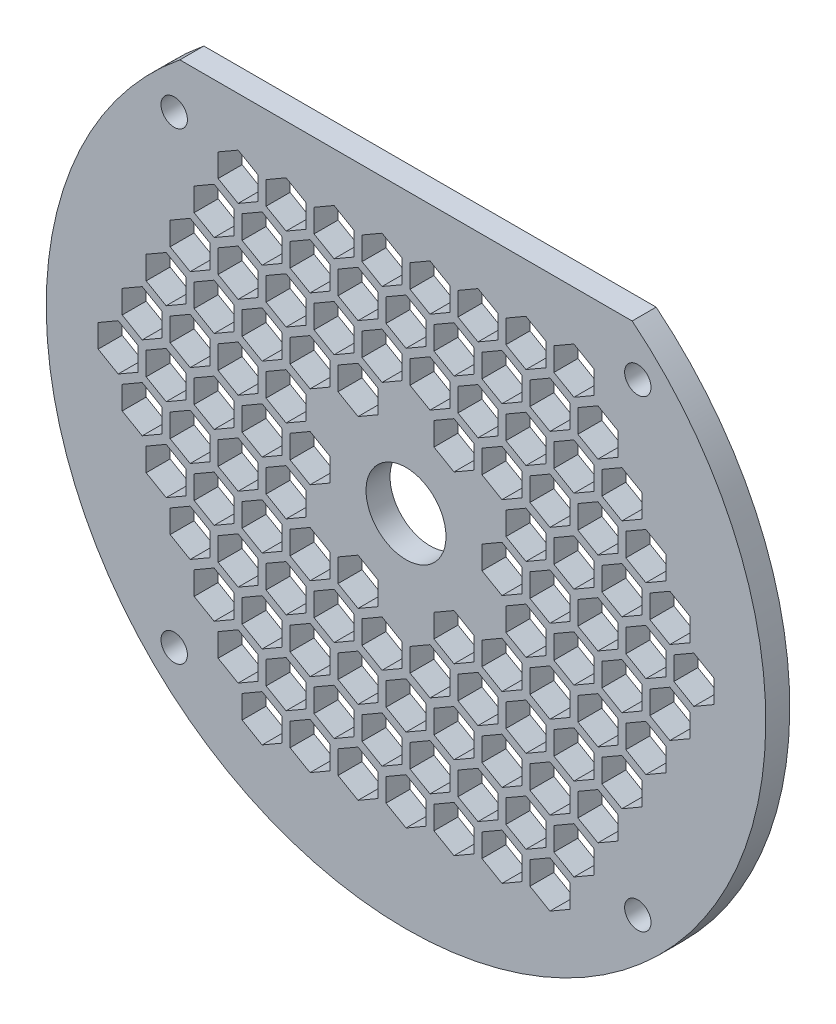
SolidWorks part; units mm, degrees
ref_plane "前视基准面" through (0, 0, 0) normal (0, 0, 1) x (1, 0, 0)
ref_plane "上视基准面" through (0, 0, 0) normal (0, 1, 0) x (1, 0, 0)
ref_plane "右视基准面" through (0, 0, 0) normal (1, 0, 0) x (0, 0, -1)
sketch "草图1" plane through (0, 0, 0) normal (0, 0, 1) x (1, 0, 0)
  circle A0 centre (0, 0) radius 90
extrude "凸台-拉伸1" add sketch "草图1" along normal blind 6
sketch "草图2" plane through (0, 0, 0) normal (0, 0, 1) x (1, 0, 0)
  line L0 (-200, 70) -> (200, 70)
  line L1 (200, 70) -> (200, 310)
  line L2 (200, 310) -> (-200, 310)
  line L3 (-200, 310) -> (-200, 70)
extrude "切除-拉伸1" cut sketch "草图2" along normal blind 6
sketch "草图3" plane through (0, 0, 0) normal (0, 0, 1) x (1, 0, 0)
  line L0 (24, 5.7735) -> (19, 2.8868)
  line L1 (19, 2.8868) -> (19, -2.8868)
  line L2 (19, -2.8868) -> (24, -5.7735)
  line L3 (24, -5.7735) -> (29, -2.8868)
  line L4 (29, -2.8868) -> (29, 2.8868)
  line L5 (29, 2.8868) -> (24, 5.7735)
  line L6 (-24, 5.7735) -> (-29, 2.8868)
  line L7 (-29, 2.8868) -> (-29, -2.8868)
  line L8 (-29, -2.8868) -> (-24, -5.7735)
  line L9 (-24, -5.7735) -> (-19, -2.8868)
  line L10 (-19, -2.8868) -> (-19, 2.8868)
  line L11 (-19, 2.8868) -> (-24, 5.7735)
  line L12 (36, 5.7735) -> (31, 2.8868)
  line L13 (31, 2.8868) -> (31, -2.8868)
  line L14 (31, -2.8868) -> (36, -5.7735)
  line L15 (36, -5.7735) -> (41, -2.8868)
  line L16 (41, -2.8868) -> (41, 2.8868)
  line L17 (41, 2.8868) -> (36, 5.7735)
  line L18 (-36, 5.7735) -> (-41, 2.8868)
  line L19 (-41, 2.8868) -> (-41, -2.8868)
  line L20 (-41, -2.8868) -> (-36, -5.7735)
  line L21 (-36, -5.7735) -> (-31, -2.8868)
  line L22 (-31, -2.8868) -> (-31, 2.8868)
  line L23 (-31, 2.8868) -> (-36, 5.7735)
  line L24 (48, 5.7735) -> (43, 2.8868)
  line L25 (43, 2.8868) -> (43, -2.8868)
  line L26 (43, -2.8868) -> (48, -5.7735)
  line L27 (48, -5.7735) -> (53, -2.8868)
  line L28 (53, -2.8868) -> (53, 2.8868)
  line L29 (53, 2.8868) -> (48, 5.7735)
  line L30 (-48, 5.7735) -> (-53, 2.8868)
  line L31 (-53, 2.8868) -> (-53, -2.8868)
  line L32 (-53, -2.8868) -> (-48, -5.7735)
  line L33 (-48, -5.7735) -> (-43, -2.8868)
  line L34 (-43, -2.8868) -> (-43, 2.8868)
  line L35 (-43, 2.8868) -> (-48, 5.7735)
  line L36 (60, 5.7735) -> (55, 2.8868)
  line L37 (55, 2.8868) -> (55, -2.8868)
  line L38 (55, -2.8868) -> (60, -5.7735)
  line L39 (60, -5.7735) -> (65, -2.8868)
  line L40 (65, -2.8868) -> (65, 2.8868)
  line L41 (65, 2.8868) -> (60, 5.7735)
  line L42 (-60, 5.7735) -> (-65, 2.8868)
  line L43 (-65, 2.8868) -> (-65, -2.8868)
  line L44 (-65, -2.8868) -> (-60, -5.7735)
  line L45 (-60, -5.7735) -> (-55, -2.8868)
  line L46 (-55, -2.8868) -> (-55, 2.8868)
  line L47 (-55, 2.8868) -> (-60, 5.7735)
  line L48 (72, 5.7735) -> (67, 2.8868)
  line L49 (67, 2.8868) -> (67, -2.8868)
  line L50 (67, -2.8868) -> (72, -5.7735)
  line L51 (72, -5.7735) -> (77, -2.8868)
  line L52 (77, -2.8868) -> (77, 2.8868)
  line L53 (77, 2.8868) -> (72, 5.7735)
  line L54 (-72, 5.7735) -> (-77, 2.8868)
  line L55 (-77, 2.8868) -> (-77, -2.8868)
  line L56 (-77, -2.8868) -> (-72, -5.7735)
  line L57 (-72, -5.7735) -> (-67, -2.8868)
  line L58 (-67, -2.8868) -> (-67, 2.8868)
  line L59 (-67, 2.8868) -> (-72, 5.7735)
  line L60 (30, 16.1655) -> (25, 13.2788)
  line L61 (25, 13.2788) -> (25, 7.5053)
  line L62 (25, 7.5053) -> (30, 4.6185)
  line L63 (30, 4.6185) -> (35, 7.5053)
  line L64 (35, 7.5053) -> (35, 13.2788)
  line L65 (35, 13.2788) -> (30, 16.1655)
  line L66 (-30, 16.1655) -> (-35, 13.2788)
  line L67 (-35, 13.2788) -> (-35, 7.5053)
  line L68 (-35, 7.5053) -> (-30, 4.6185)
  line L69 (-30, 4.6185) -> (-25, 7.5053)
  line L70 (-25, 7.5053) -> (-25, 13.2788)
  line L71 (-25, 13.2788) -> (-30, 16.1655)
  line L72 (42, 16.1655) -> (37, 13.2788)
  line L73 (37, 13.2788) -> (37, 7.5053)
  line L74 (37, 7.5053) -> (42, 4.6185)
  line L75 (42, 4.6185) -> (47, 7.5053)
  line L76 (47, 7.5053) -> (47, 13.2788)
  line L77 (47, 13.2788) -> (42, 16.1655)
  line L78 (-42, 16.1655) -> (-47, 13.2788)
  line L79 (-47, 13.2788) -> (-47, 7.5053)
  line L80 (-47, 7.5053) -> (-42, 4.6185)
  line L81 (-42, 4.6185) -> (-37, 7.5053)
  line L82 (-37, 7.5053) -> (-37, 13.2788)
  line L83 (-37, 13.2788) -> (-42, 16.1655)
  line L84 (54, 16.1655) -> (49, 13.2788)
  line L85 (49, 13.2788) -> (49, 7.5053)
  line L86 (49, 7.5053) -> (54, 4.6185)
  line L87 (54, 4.6185) -> (59, 7.5053)
  line L88 (59, 7.5053) -> (59, 13.2788)
  line L89 (59, 13.2788) -> (54, 16.1655)
  line L90 (-54, 16.1655) -> (-59, 13.2788)
  line L91 (-59, 13.2788) -> (-59, 7.5053)
  line L92 (-59, 7.5053) -> (-54, 4.6185)
  line L93 (-54, 4.6185) -> (-49, 7.5053)
  line L94 (-49, 7.5053) -> (-49, 13.2788)
  line L95 (-49, 13.2788) -> (-54, 16.1655)
  line L96 (66, 16.1655) -> (61, 13.2788)
  line L97 (61, 13.2788) -> (61, 7.5053)
  line L98 (61, 7.5053) -> (66, 4.6185)
  line L99 (66, 4.6185) -> (71, 7.5053)
  line L100 (71, 7.5053) -> (71, 13.2788)
  line L101 (71, 13.2788) -> (66, 16.1655)
  line L102 (-66, 16.1655) -> (-71, 13.2788)
  line L103 (-71, 13.2788) -> (-71, 7.5053)
  line L104 (-71, 7.5053) -> (-66, 4.6185)
  line L105 (-66, 4.6185) -> (-61, 7.5053)
  line L106 (-61, 7.5053) -> (-61, 13.2788)
  line L107 (-61, 13.2788) -> (-66, 16.1655)
  line L108 (30, -4.6185) -> (25, -7.5053)
  line L109 (25, -7.5053) -> (25, -13.2788)
  line L110 (25, -13.2788) -> (30, -16.1655)
  line L111 (30, -16.1655) -> (35, -13.2788)
  line L112 (35, -13.2788) -> (35, -7.5053)
  line L113 (35, -7.5053) -> (30, -4.6185)
  line L114 (-30, -4.6185) -> (-35, -7.5053)
  line L115 (-35, -7.5053) -> (-35, -13.2788)
  line L116 (-35, -13.2788) -> (-30, -16.1655)
  line L117 (-30, -16.1655) -> (-25, -13.2788)
  line L118 (-25, -13.2788) -> (-25, -7.5053)
  line L119 (-25, -7.5053) -> (-30, -4.6185)
  line L120 (42, -4.6185) -> (37, -7.5053)
  line L121 (37, -7.5053) -> (37, -13.2788)
  line L122 (37, -13.2788) -> (42, -16.1655)
  line L123 (42, -16.1655) -> (47, -13.2788)
  line L124 (47, -13.2788) -> (47, -7.5053)
  line L125 (47, -7.5053) -> (42, -4.6185)
  line L126 (-42, -4.6185) -> (-47, -7.5053)
  line L127 (-47, -7.5053) -> (-47, -13.2788)
  line L128 (-47, -13.2788) -> (-42, -16.1655)
  line L129 (-42, -16.1655) -> (-37, -13.2788)
  line L130 (-37, -13.2788) -> (-37, -7.5053)
  line L131 (-37, -7.5053) -> (-42, -4.6185)
  line L132 (54, -4.6185) -> (49, -7.5053)
  line L133 (49, -7.5053) -> (49, -13.2788)
  line L134 (49, -13.2788) -> (54, -16.1655)
  line L135 (54, -16.1655) -> (59, -13.2788)
  line L136 (59, -13.2788) -> (59, -7.5053)
  line L137 (59, -7.5053) -> (54, -4.6185)
  line L138 (-54, -4.6185) -> (-59, -7.5053)
  line L139 (-59, -7.5053) -> (-59, -13.2788)
  line L140 (-59, -13.2788) -> (-54, -16.1655)
  line L141 (-54, -16.1655) -> (-49, -13.2788)
  line L142 (-49, -13.2788) -> (-49, -7.5053)
  line L143 (-49, -7.5053) -> (-54, -4.6185)
  line L144 (66, -4.6185) -> (61, -7.5053)
  line L145 (61, -7.5053) -> (61, -13.2788)
  line L146 (61, -13.2788) -> (66, -16.1655)
  line L147 (66, -16.1655) -> (71, -13.2788)
  line L148 (71, -13.2788) -> (71, -7.5053)
  line L149 (71, -7.5053) -> (66, -4.6185)
  line L150 (-66, -4.6185) -> (-71, -7.5053)
  line L151 (-71, -7.5053) -> (-71, -13.2788)
  line L152 (-71, -13.2788) -> (-66, -16.1655)
  line L153 (-66, -16.1655) -> (-61, -13.2788)
  line L154 (-61, -13.2788) -> (-61, -7.5053)
  line L155 (-61, -7.5053) -> (-66, -4.6185)
extrude "切除-拉伸2" cut sketch "草图3" against normal mid plane 362
sketch "草图4" plane through (0, 0, 0) normal (0, 0, 1) x (1, 0, 0)
  line L0 (-60, 26.5575) -> (-65, 23.6708)
  line L1 (-65, 23.6708) -> (-65, 17.8972)
  line L2 (-65, 17.8972) -> (-60, 15.0105)
  line L3 (-60, 15.0105) -> (-55, 17.8972)
  line L4 (-55, 17.8972) -> (-55, 23.6708)
  line L5 (-55, 23.6708) -> (-60, 26.5575)
  line L6 (-48, 26.5575) -> (-53, 23.6708)
  line L7 (-53, 23.6708) -> (-53, 17.8972)
  line L8 (-53, 17.8972) -> (-48, 15.0105)
  line L9 (-48, 15.0105) -> (-43, 17.8972)
  line L10 (-43, 17.8972) -> (-43, 23.6708)
  line L11 (-43, 23.6708) -> (-48, 26.5575)
  line L12 (-36, 26.5575) -> (-41, 23.6708)
  line L13 (-41, 23.6708) -> (-41, 17.8972)
  line L14 (-41, 17.8972) -> (-36, 15.0105)
  line L15 (-36, 15.0105) -> (-31, 17.8972)
  line L16 (-31, 17.8972) -> (-31, 23.6708)
  line L17 (-31, 23.6708) -> (-36, 26.5575)
  line L18 (-24, 26.5575) -> (-29, 23.6708)
  line L19 (-29, 23.6708) -> (-29, 17.8972)
  line L20 (-29, 17.8972) -> (-24, 15.0105)
  line L21 (-24, 15.0105) -> (-19, 17.8972)
  line L22 (-19, 17.8972) -> (-19, 23.6708)
  line L23 (-19, 23.6708) -> (-24, 26.5575)
  line L24 (-12, 26.5575) -> (-17, 23.6708)
  line L25 (-17, 23.6708) -> (-17, 17.8972)
  line L26 (-17, 17.8972) -> (-12, 15.0105)
  line L27 (-12, 15.0105) -> (-7, 17.8972)
  line L28 (-7, 17.8972) -> (-7, 23.6708)
  line L29 (-7, 23.6708) -> (-12, 26.5575)
  line L30 (0, 26.5575) -> (-5, 23.6708)
  line L31 (-5, 23.6708) -> (-5, 17.8972)
  line L32 (-5, 17.8972) -> (0, 15.0105)
  line L33 (0, 15.0105) -> (5, 17.8972)
  line L34 (5, 17.8972) -> (5, 23.6708)
  line L35 (5, 23.6708) -> (0, 26.5575)
  line L36 (12, 26.5575) -> (7, 23.6708)
  line L37 (7, 23.6708) -> (7, 17.8972)
  line L38 (7, 17.8972) -> (12, 15.0105)
  line L39 (12, 15.0105) -> (17, 17.8972)
  line L40 (17, 17.8972) -> (17, 23.6708)
  line L41 (17, 23.6708) -> (12, 26.5575)
  line L42 (24, 26.5575) -> (19, 23.6708)
  line L43 (19, 23.6708) -> (19, 17.8972)
  line L44 (19, 17.8972) -> (24, 15.0105)
  line L45 (24, 15.0105) -> (29, 17.8972)
  line L46 (29, 17.8972) -> (29, 23.6708)
  line L47 (29, 23.6708) -> (24, 26.5575)
  line L48 (36, 26.5575) -> (31, 23.6708)
  line L49 (31, 23.6708) -> (31, 17.8972)
  line L50 (31, 17.8972) -> (36, 15.0105)
  line L51 (36, 15.0105) -> (41, 17.8972)
  line L52 (41, 17.8972) -> (41, 23.6708)
  line L53 (41, 23.6708) -> (36, 26.5575)
  line L54 (48, 26.5575) -> (43, 23.6708)
  line L55 (43, 23.6708) -> (43, 17.8972)
  line L56 (43, 17.8972) -> (48, 15.0105)
  line L57 (48, 15.0105) -> (53, 17.8972)
  line L58 (53, 17.8972) -> (53, 23.6708)
  line L59 (53, 23.6708) -> (48, 26.5575)
  line L60 (60, 26.5575) -> (55, 23.6708)
  line L61 (55, 23.6708) -> (55, 17.8972)
  line L62 (55, 17.8972) -> (60, 15.0105)
  line L63 (60, 15.0105) -> (65, 17.8972)
  line L64 (65, 17.8972) -> (65, 23.6708)
  line L65 (65, 23.6708) -> (60, 26.5575)
  line L66 (-60, -15.0105) -> (-65, -17.8972)
  line L67 (-65, -17.8972) -> (-65, -23.6708)
  line L68 (-65, -23.6708) -> (-60, -26.5575)
  line L69 (-60, -26.5575) -> (-55, -23.6708)
  line L70 (-55, -23.6708) -> (-55, -17.8972)
  line L71 (-55, -17.8972) -> (-60, -15.0105)
  line L72 (-48, -15.0105) -> (-53, -17.8972)
  line L73 (-53, -17.8972) -> (-53, -23.6708)
  line L74 (-53, -23.6708) -> (-48, -26.5575)
  line L75 (-48, -26.5575) -> (-43, -23.6708)
  line L76 (-43, -23.6708) -> (-43, -17.8972)
  line L77 (-43, -17.8972) -> (-48, -15.0105)
  line L78 (-36, -15.0105) -> (-41, -17.8972)
  line L79 (-41, -17.8972) -> (-41, -23.6708)
  line L80 (-41, -23.6708) -> (-36, -26.5575)
  line L81 (-36, -26.5575) -> (-31, -23.6708)
  line L82 (-31, -23.6708) -> (-31, -17.8972)
  line L83 (-31, -17.8972) -> (-36, -15.0105)
  line L84 (-24, -15.0105) -> (-29, -17.8972)
  line L85 (-29, -17.8972) -> (-29, -23.6708)
  line L86 (-29, -23.6708) -> (-24, -26.5575)
  line L87 (-24, -26.5575) -> (-19, -23.6708)
  line L88 (-19, -23.6708) -> (-19, -17.8972)
  line L89 (-19, -17.8972) -> (-24, -15.0105)
  line L90 (-12, -15.0105) -> (-17, -17.8972)
  line L91 (-17, -17.8972) -> (-17, -23.6708)
  line L92 (-17, -23.6708) -> (-12, -26.5575)
  line L93 (-12, -26.5575) -> (-7, -23.6708)
  line L94 (-7, -23.6708) -> (-7, -17.8972)
  line L95 (-7, -17.8972) -> (-12, -15.0105)
  line L96 (0, -15.0105) -> (-5, -17.8972)
  line L97 (-5, -17.8972) -> (-5, -23.6708)
  line L98 (-5, -23.6708) -> (0, -26.5575)
  line L99 (0, -26.5575) -> (5, -23.6708)
  line L100 (5, -23.6708) -> (5, -17.8972)
  line L101 (5, -17.8972) -> (0, -15.0105)
  line L102 (12, -15.0105) -> (7, -17.8972)
  line L103 (7, -17.8972) -> (7, -23.6708)
  line L104 (7, -23.6708) -> (12, -26.5575)
  line L105 (12, -26.5575) -> (17, -23.6708)
  line L106 (17, -23.6708) -> (17, -17.8972)
  line L107 (17, -17.8972) -> (12, -15.0105)
  line L108 (24, -15.0105) -> (19, -17.8972)
  line L109 (19, -17.8972) -> (19, -23.6708)
  line L110 (19, -23.6708) -> (24, -26.5575)
  line L111 (24, -26.5575) -> (29, -23.6708)
  line L112 (29, -23.6708) -> (29, -17.8972)
  line L113 (29, -17.8972) -> (24, -15.0105)
  line L114 (36, -15.0105) -> (31, -17.8972)
  line L115 (31, -17.8972) -> (31, -23.6708)
  line L116 (31, -23.6708) -> (36, -26.5575)
  line L117 (36, -26.5575) -> (41, -23.6708)
  line L118 (41, -23.6708) -> (41, -17.8972)
  line L119 (41, -17.8972) -> (36, -15.0105)
  line L120 (48, -15.0105) -> (43, -17.8972)
  line L121 (43, -17.8972) -> (43, -23.6708)
  line L122 (43, -23.6708) -> (48, -26.5575)
  line L123 (48, -26.5575) -> (53, -23.6708)
  line L124 (53, -23.6708) -> (53, -17.8972)
  line L125 (53, -17.8972) -> (48, -15.0105)
  line L126 (60, -15.0105) -> (55, -17.8972)
  line L127 (55, -17.8972) -> (55, -23.6708)
  line L128 (55, -23.6708) -> (60, -26.5575)
  line L129 (60, -26.5575) -> (65, -23.6708)
  line L130 (65, -23.6708) -> (65, -17.8972)
  line L131 (65, -17.8972) -> (60, -15.0105)
extrude "切除-拉伸3" cut sketch "草图4" against normal mid plane 362
sketch "草图5" plane through (0, 0, 0) normal (0, 0, 1) x (1, 0, 0)
  line L0 (0, 26.5575) -> (-5, 23.6708)
  line L1 (-5, 23.6708) -> (-5, 17.8972)
  line L2 (-5, 17.8972) -> (0, 15.0105)
  line L3 (0, 15.0105) -> (5, 17.8972)
  line L4 (5, 17.8972) -> (5, 23.6708)
  line L5 (5, 23.6708) -> (0, 26.5575)
  line L6 (0, -15.0105) -> (-5, -17.8972)
  line L7 (-5, -17.8972) -> (-5, -23.6708)
  line L8 (-5, -23.6708) -> (0, -26.5575)
  line L9 (0, -26.5575) -> (5, -23.6708)
  line L10 (5, -23.6708) -> (5, -17.8972)
  line L11 (5, -17.8972) -> (0, -15.0105)
extrude "凸台-拉伸2" add sketch "草图5" along normal blind 6
sketch "草图7" plane through (0, 0, 0) normal (0, 0, 1) x (1, 0, 0)
  line L0 (6, 36.9495) -> (1, 34.0628)
  line L1 (1, 34.0628) -> (1, 28.2892)
  line L2 (1, 28.2892) -> (6, 25.4025)
  line L3 (6, 25.4025) -> (11, 28.2892)
  line L4 (11, 28.2892) -> (11, 34.0628)
  line L5 (11, 34.0628) -> (6, 36.9495)
  line L6 (-6, 36.9495) -> (-11, 34.0628)
  line L7 (-11, 34.0628) -> (-11, 28.2892)
  line L8 (-11, 28.2892) -> (-6, 25.4025)
  line L9 (-6, 25.4025) -> (-1, 28.2892)
  line L10 (-1, 28.2892) -> (-1, 34.0628)
  line L11 (-1, 34.0628) -> (-6, 36.9495)
  line L12 (18, 36.9495) -> (13, 34.0628)
  line L13 (13, 34.0628) -> (13, 28.2892)
  line L14 (13, 28.2892) -> (18, 25.4025)
  line L15 (18, 25.4025) -> (23, 28.2892)
  line L16 (23, 28.2892) -> (23, 34.0628)
  line L17 (23, 34.0628) -> (18, 36.9495)
  line L18 (-18, 36.9495) -> (-23, 34.0628)
  line L19 (-23, 34.0628) -> (-23, 28.2892)
  line L20 (-23, 28.2892) -> (-18, 25.4025)
  line L21 (-18, 25.4025) -> (-13, 28.2892)
  line L22 (-13, 28.2892) -> (-13, 34.0628)
  line L23 (-13, 34.0628) -> (-18, 36.9495)
  line L24 (30, 36.9495) -> (25, 34.0628)
  line L25 (25, 34.0628) -> (25, 28.2892)
  line L26 (25, 28.2892) -> (30, 25.4025)
  line L27 (30, 25.4025) -> (35, 28.2892)
  line L28 (35, 28.2892) -> (35, 34.0628)
  line L29 (35, 34.0628) -> (30, 36.9495)
  line L30 (-30, 36.9495) -> (-35, 34.0628)
  line L31 (-35, 34.0628) -> (-35, 28.2892)
  line L32 (-35, 28.2892) -> (-30, 25.4025)
  line L33 (-30, 25.4025) -> (-25, 28.2892)
  line L34 (-25, 28.2892) -> (-25, 34.0628)
  line L35 (-25, 34.0628) -> (-30, 36.9495)
  line L36 (42, 36.9495) -> (37, 34.0628)
  line L37 (37, 34.0628) -> (37, 28.2892)
  line L38 (37, 28.2892) -> (42, 25.4025)
  line L39 (42, 25.4025) -> (47, 28.2892)
  line L40 (47, 28.2892) -> (47, 34.0628)
  line L41 (47, 34.0628) -> (42, 36.9495)
  line L42 (-42, 36.9495) -> (-47, 34.0628)
  line L43 (-47, 34.0628) -> (-47, 28.2892)
  line L44 (-47, 28.2892) -> (-42, 25.4025)
  line L45 (-42, 25.4025) -> (-37, 28.2892)
  line L46 (-37, 28.2892) -> (-37, 34.0628)
  line L47 (-37, 34.0628) -> (-42, 36.9495)
  line L48 (54, 36.9495) -> (49, 34.0628)
  line L49 (49, 34.0628) -> (49, 28.2892)
  line L50 (49, 28.2892) -> (54, 25.4025)
  line L51 (54, 25.4025) -> (59, 28.2892)
  line L52 (59, 28.2892) -> (59, 34.0628)
  line L53 (59, 34.0628) -> (54, 36.9495)
  line L54 (-54, 36.9495) -> (-59, 34.0628)
  line L55 (-59, 34.0628) -> (-59, 28.2892)
  line L56 (-59, 28.2892) -> (-54, 25.4025)
  line L57 (-54, 25.4025) -> (-49, 28.2892)
  line L58 (-49, 28.2892) -> (-49, 34.0628)
  line L59 (-49, 34.0628) -> (-54, 36.9495)
  line L60 (6, -25.4025) -> (1, -28.2892)
  line L61 (1, -28.2892) -> (1, -34.0628)
  line L62 (1, -34.0628) -> (6, -36.9495)
  line L63 (6, -36.9495) -> (11, -34.0628)
  line L64 (11, -34.0628) -> (11, -28.2892)
  line L65 (11, -28.2892) -> (6, -25.4025)
  line L66 (-6, -25.4025) -> (-11, -28.2892)
  line L67 (-11, -28.2892) -> (-11, -34.0628)
  line L68 (-11, -34.0628) -> (-6, -36.9495)
  line L69 (-6, -36.9495) -> (-1, -34.0628)
  line L70 (-1, -34.0628) -> (-1, -28.2892)
  line L71 (-1, -28.2892) -> (-6, -25.4025)
  line L72 (18, -25.4025) -> (13, -28.2892)
  line L73 (13, -28.2892) -> (13, -34.0628)
  line L74 (13, -34.0628) -> (18, -36.9495)
  line L75 (18, -36.9495) -> (23, -34.0628)
  line L76 (23, -34.0628) -> (23, -28.2892)
  line L77 (23, -28.2892) -> (18, -25.4025)
  line L78 (-18, -25.4025) -> (-23, -28.2892)
  line L79 (-23, -28.2892) -> (-23, -34.0628)
  line L80 (-23, -34.0628) -> (-18, -36.9495)
  line L81 (-18, -36.9495) -> (-13, -34.0628)
  line L82 (-13, -34.0628) -> (-13, -28.2892)
  line L83 (-13, -28.2892) -> (-18, -25.4025)
  line L84 (30, -25.4025) -> (25, -28.2892)
  line L85 (25, -28.2892) -> (25, -34.0628)
  line L86 (25, -34.0628) -> (30, -36.9495)
  line L87 (30, -36.9495) -> (35, -34.0628)
  line L88 (35, -34.0628) -> (35, -28.2892)
  line L89 (35, -28.2892) -> (30, -25.4025)
  line L90 (-30, -25.4025) -> (-35, -28.2892)
  line L91 (-35, -28.2892) -> (-35, -34.0628)
  line L92 (-35, -34.0628) -> (-30, -36.9495)
  line L93 (-30, -36.9495) -> (-25, -34.0628)
  line L94 (-25, -34.0628) -> (-25, -28.2892)
  line L95 (-25, -28.2892) -> (-30, -25.4025)
  line L96 (42, -25.4025) -> (37, -28.2892)
  line L97 (37, -28.2892) -> (37, -34.0628)
  line L98 (37, -34.0628) -> (42, -36.9495)
  line L99 (42, -36.9495) -> (47, -34.0628)
  line L100 (47, -34.0628) -> (47, -28.2892)
  line L101 (47, -28.2892) -> (42, -25.4025)
  line L102 (-42, -25.4025) -> (-47, -28.2892)
  line L103 (-47, -28.2892) -> (-47, -34.0628)
  line L104 (-47, -34.0628) -> (-42, -36.9495)
  line L105 (-42, -36.9495) -> (-37, -34.0628)
  line L106 (-37, -34.0628) -> (-37, -28.2892)
  line L107 (-37, -28.2892) -> (-42, -25.4025)
  line L108 (54, -25.4025) -> (49, -28.2892)
  line L109 (49, -28.2892) -> (49, -34.0628)
  line L110 (49, -34.0628) -> (54, -36.9495)
  line L111 (54, -36.9495) -> (59, -34.0628)
  line L112 (59, -34.0628) -> (59, -28.2892)
  line L113 (59, -28.2892) -> (54, -25.4025)
  line L114 (-54, -25.4025) -> (-59, -28.2892)
  line L115 (-59, -28.2892) -> (-59, -34.0628)
  line L116 (-59, -34.0628) -> (-54, -36.9495)
  line L117 (-54, -36.9495) -> (-49, -34.0628)
  line L118 (-49, -34.0628) -> (-49, -28.2892)
  line L119 (-49, -28.2892) -> (-54, -25.4025)
extrude "切除-拉伸6" cut sketch "草图7" against normal mid plane 362
sketch "草图8" plane through (0, 0, 0) normal (0, 0, 1) x (1, 0, 0)
  line L0 (0, 47.3415) -> (-5, 44.4547)
  line L1 (-5, 44.4547) -> (-5, 38.6812)
  line L2 (-5, 38.6812) -> (0, 35.7945)
  line L3 (0, 35.7945) -> (5, 38.6812)
  line L4 (5, 38.6812) -> (5, 44.4547)
  line L5 (5, 44.4547) -> (0, 47.3415)
  line L6 (12, 47.3415) -> (7, 44.4547)
  line L7 (7, 44.4547) -> (7, 38.6812)
  line L8 (7, 38.6812) -> (12, 35.7945)
  line L9 (12, 35.7945) -> (17, 38.6812)
  line L10 (17, 38.6812) -> (17, 44.4547)
  line L11 (17, 44.4547) -> (12, 47.3415)
  line L12 (-12, 47.3415) -> (-17, 44.4547)
  line L13 (-17, 44.4547) -> (-17, 38.6812)
  line L14 (-17, 38.6812) -> (-12, 35.7945)
  line L15 (-12, 35.7945) -> (-7, 38.6812)
  line L16 (-7, 38.6812) -> (-7, 44.4547)
  line L17 (-7, 44.4547) -> (-12, 47.3415)
  line L18 (24, 47.3415) -> (19, 44.4547)
  line L19 (19, 44.4547) -> (19, 38.6812)
  line L20 (19, 38.6812) -> (24, 35.7945)
  line L21 (24, 35.7945) -> (29, 38.6812)
  line L22 (29, 38.6812) -> (29, 44.4547)
  line L23 (29, 44.4547) -> (24, 47.3415)
  line L24 (-24, 47.3415) -> (-29, 44.4547)
  line L25 (-29, 44.4547) -> (-29, 38.6812)
  line L26 (-29, 38.6812) -> (-24, 35.7945)
  line L27 (-24, 35.7945) -> (-19, 38.6812)
  line L28 (-19, 38.6812) -> (-19, 44.4547)
  line L29 (-19, 44.4547) -> (-24, 47.3415)
  line L30 (36, 47.3415) -> (31, 44.4547)
  line L31 (31, 44.4547) -> (31, 38.6812)
  line L32 (31, 38.6812) -> (36, 35.7945)
  line L33 (36, 35.7945) -> (41, 38.6812)
  line L34 (41, 38.6812) -> (41, 44.4547)
  line L35 (41, 44.4547) -> (36, 47.3415)
  line L36 (-36, 47.3415) -> (-41, 44.4547)
  line L37 (-41, 44.4547) -> (-41, 38.6812)
  line L38 (-41, 38.6812) -> (-36, 35.7945)
  line L39 (-36, 35.7945) -> (-31, 38.6812)
  line L40 (-31, 38.6812) -> (-31, 44.4547)
  line L41 (-31, 44.4547) -> (-36, 47.3415)
  line L42 (48, 47.3415) -> (43, 44.4547)
  line L43 (43, 44.4547) -> (43, 38.6812)
  line L44 (43, 38.6812) -> (48, 35.7945)
  line L45 (48, 35.7945) -> (53, 38.6812)
  line L46 (53, 38.6812) -> (53, 44.4547)
  line L47 (53, 44.4547) -> (48, 47.3415)
  line L48 (-48, 47.3415) -> (-53, 44.4547)
  line L49 (-53, 44.4547) -> (-53, 38.6812)
  line L50 (-53, 38.6812) -> (-48, 35.7945)
  line L51 (-48, 35.7945) -> (-43, 38.6812)
  line L52 (-43, 38.6812) -> (-43, 44.4547)
  line L53 (-43, 44.4547) -> (-48, 47.3415)
  line L54 (0, -35.7945) -> (-5, -38.6812)
  line L55 (-5, -38.6812) -> (-5, -44.4547)
  line L56 (-5, -44.4547) -> (0, -47.3415)
  line L57 (0, -47.3415) -> (5, -44.4547)
  line L58 (5, -44.4547) -> (5, -38.6812)
  line L59 (5, -38.6812) -> (0, -35.7945)
  line L60 (12, -35.7945) -> (7, -38.6812)
  line L61 (7, -38.6812) -> (7, -44.4547)
  line L62 (7, -44.4547) -> (12, -47.3415)
  line L63 (12, -47.3415) -> (17, -44.4547)
  line L64 (17, -44.4547) -> (17, -38.6812)
  line L65 (17, -38.6812) -> (12, -35.7945)
  line L66 (-12, -35.7945) -> (-17, -38.6812)
  line L67 (-17, -38.6812) -> (-17, -44.4547)
  line L68 (-17, -44.4547) -> (-12, -47.3415)
  line L69 (-12, -47.3415) -> (-7, -44.4547)
  line L70 (-7, -44.4547) -> (-7, -38.6812)
  line L71 (-7, -38.6812) -> (-12, -35.7945)
  line L72 (24, -35.7945) -> (19, -38.6812)
  line L73 (19, -38.6812) -> (19, -44.4547)
  line L74 (19, -44.4547) -> (24, -47.3415)
  line L75 (24, -47.3415) -> (29, -44.4547)
  line L76 (29, -44.4547) -> (29, -38.6812)
  line L77 (29, -38.6812) -> (24, -35.7945)
  line L78 (-24, -35.7945) -> (-29, -38.6812)
  line L79 (-29, -38.6812) -> (-29, -44.4547)
  line L80 (-29, -44.4547) -> (-24, -47.3415)
  line L81 (-24, -47.3415) -> (-19, -44.4547)
  line L82 (-19, -44.4547) -> (-19, -38.6812)
  line L83 (-19, -38.6812) -> (-24, -35.7945)
  line L84 (36, -35.7945) -> (31, -38.6812)
  line L85 (31, -38.6812) -> (31, -44.4547)
  line L86 (31, -44.4547) -> (36, -47.3415)
  line L87 (36, -47.3415) -> (41, -44.4547)
  line L88 (41, -44.4547) -> (41, -38.6812)
  line L89 (41, -38.6812) -> (36, -35.7945)
  line L90 (-36, -35.7945) -> (-41, -38.6812)
  line L91 (-41, -38.6812) -> (-41, -44.4547)
  line L92 (-41, -44.4547) -> (-36, -47.3415)
  line L93 (-36, -47.3415) -> (-31, -44.4547)
  line L94 (-31, -44.4547) -> (-31, -38.6812)
  line L95 (-31, -38.6812) -> (-36, -35.7945)
  line L96 (48, -35.7945) -> (43, -38.6812)
  line L97 (43, -38.6812) -> (43, -44.4547)
  line L98 (43, -44.4547) -> (48, -47.3415)
  line L99 (48, -47.3415) -> (53, -44.4547)
  line L100 (53, -44.4547) -> (53, -38.6812)
  line L101 (53, -38.6812) -> (48, -35.7945)
  line L102 (-48, -35.7945) -> (-53, -38.6812)
  line L103 (-53, -38.6812) -> (-53, -44.4547)
  line L104 (-53, -44.4547) -> (-48, -47.3415)
  line L105 (-48, -47.3415) -> (-43, -44.4547)
  line L106 (-43, -44.4547) -> (-43, -38.6812)
  line L107 (-43, -38.6812) -> (-48, -35.7945)
extrude "切除-拉伸7" cut sketch "草图8" against normal mid plane 362
sketch "草图9" plane through (0, 0, 0) normal (0, 0, 1) x (1, 0, 0)
  line L0 (5, 44.4547) -> (0, 47.3415)
  line L1 (0, 47.3415) -> (-5, 44.4547)
  line L2 (-5, 44.4547) -> (-5, 38.6812)
  line L3 (-5, 38.6812) -> (0, 35.7945)
  line L4 (0, 35.7945) -> (5, 38.6812)
  line L5 (5, 38.6812) -> (5, 44.4547)
  line L6 (17, 44.4547) -> (12, 47.3415)
  line L7 (12, 47.3415) -> (7, 44.4547)
  line L8 (7, 44.4547) -> (7, 38.6812)
  line L9 (7, 38.6812) -> (12, 35.7945)
  line L10 (12, 35.7945) -> (17, 38.6812)
  line L11 (17, 38.6812) -> (17, 44.4547)
  line L12 (-7, 44.4547) -> (-12, 47.3415)
  line L13 (-12, 47.3415) -> (-17, 44.4547)
  line L14 (-17, 44.4547) -> (-17, 38.6812)
  line L15 (-17, 38.6812) -> (-12, 35.7945)
  line L16 (-12, 35.7945) -> (-7, 38.6812)
  line L17 (-7, 38.6812) -> (-7, 44.4547)
  line L18 (29, 44.4547) -> (24, 47.3415)
  line L19 (24, 47.3415) -> (19, 44.4547)
  line L20 (19, 44.4547) -> (19, 38.6812)
  line L21 (19, 38.6812) -> (24, 35.7945)
  line L22 (24, 35.7945) -> (29, 38.6812)
  line L23 (29, 38.6812) -> (29, 44.4547)
  line L24 (-19, 44.4547) -> (-24, 47.3415)
  line L25 (-24, 47.3415) -> (-29, 44.4547)
  line L26 (-29, 44.4547) -> (-29, 38.6812)
  line L27 (-29, 38.6812) -> (-24, 35.7945)
  line L28 (-24, 35.7945) -> (-19, 38.6812)
  line L29 (-19, 38.6812) -> (-19, 44.4547)
  line L30 (41, 44.4547) -> (36, 47.3415)
  line L31 (36, 47.3415) -> (31, 44.4547)
  line L32 (31, 44.4547) -> (31, 38.6812)
  line L33 (31, 38.6812) -> (36, 35.7945)
  line L34 (36, 35.7945) -> (41, 38.6812)
  line L35 (41, 38.6812) -> (41, 44.4547)
  line L36 (-31, 44.4547) -> (-36, 47.3415)
  line L37 (-36, 47.3415) -> (-41, 44.4547)
  line L38 (-41, 44.4547) -> (-41, 38.6812)
  line L39 (-41, 38.6812) -> (-36, 35.7945)
  line L40 (-36, 35.7945) -> (-31, 38.6812)
  line L41 (-31, 38.6812) -> (-31, 44.4547)
  line L42 (53, 44.4547) -> (48, 47.3415)
  line L43 (48, 47.3415) -> (43, 44.4547)
  line L44 (43, 44.4547) -> (43, 38.6812)
  line L45 (43, 38.6812) -> (48, 35.7945)
  line L46 (48, 35.7945) -> (53, 38.6812)
  line L47 (53, 38.6812) -> (53, 44.4547)
  line L48 (-43, 44.4547) -> (-48, 47.3415)
  line L49 (-48, 47.3415) -> (-53, 44.4547)
  line L50 (-53, 44.4547) -> (-53, 38.6812)
  line L51 (-53, 38.6812) -> (-48, 35.7945)
  line L52 (-48, 35.7945) -> (-43, 38.6812)
  line L53 (-43, 38.6812) -> (-43, 44.4547)
  line L54 (5, -38.6812) -> (0, -35.7945)
  line L55 (0, -35.7945) -> (-5, -38.6812)
  line L56 (-5, -38.6812) -> (-5, -44.4547)
  line L57 (-5, -44.4547) -> (0, -47.3415)
  line L58 (0, -47.3415) -> (5, -44.4547)
  line L59 (5, -44.4547) -> (5, -38.6812)
  line L60 (17, -38.6812) -> (12, -35.7945)
  line L61 (12, -35.7945) -> (7, -38.6812)
  line L62 (7, -38.6812) -> (7, -44.4547)
  line L63 (7, -44.4547) -> (12, -47.3415)
  line L64 (12, -47.3415) -> (17, -44.4547)
  line L65 (17, -44.4547) -> (17, -38.6812)
  line L66 (-7, -38.6812) -> (-12, -35.7945)
  line L67 (-12, -35.7945) -> (-17, -38.6812)
  line L68 (-17, -38.6812) -> (-17, -44.4547)
  line L69 (-17, -44.4547) -> (-12, -47.3415)
  line L70 (-12, -47.3415) -> (-7, -44.4547)
  line L71 (-7, -44.4547) -> (-7, -38.6812)
  line L72 (29, -38.6812) -> (24, -35.7945)
  line L73 (24, -35.7945) -> (19, -38.6812)
  line L74 (19, -38.6812) -> (19, -44.4547)
  line L75 (19, -44.4547) -> (24, -47.3415)
  line L76 (24, -47.3415) -> (29, -44.4547)
  line L77 (29, -44.4547) -> (29, -38.6812)
  line L78 (-19, -38.6812) -> (-24, -35.7945)
  line L79 (-24, -35.7945) -> (-29, -38.6812)
  line L80 (-29, -38.6812) -> (-29, -44.4547)
  line L81 (-29, -44.4547) -> (-24, -47.3415)
  line L82 (-24, -47.3415) -> (-19, -44.4547)
  line L83 (-19, -44.4547) -> (-19, -38.6812)
  line L84 (41, -38.6812) -> (36, -35.7945)
  line L85 (36, -35.7945) -> (31, -38.6812)
  line L86 (31, -38.6812) -> (31, -44.4547)
  line L87 (31, -44.4547) -> (36, -47.3415)
  line L88 (36, -47.3415) -> (41, -44.4547)
  line L89 (41, -44.4547) -> (41, -38.6812)
  line L90 (-31, -38.6812) -> (-36, -35.7945)
  line L91 (-36, -35.7945) -> (-41, -38.6812)
  line L92 (-41, -38.6812) -> (-41, -44.4547)
  line L93 (-41, -44.4547) -> (-36, -47.3415)
  line L94 (-36, -47.3415) -> (-31, -44.4547)
  line L95 (-31, -44.4547) -> (-31, -38.6812)
  line L96 (53, -38.6812) -> (48, -35.7945)
  line L97 (48, -35.7945) -> (43, -38.6812)
  line L98 (43, -38.6812) -> (43, -44.4547)
  line L99 (43, -44.4547) -> (48, -47.3415)
  line L100 (48, -47.3415) -> (53, -44.4547)
  line L101 (53, -44.4547) -> (53, -38.6812)
  line L102 (-43, -38.6812) -> (-48, -35.7945)
  line L103 (-48, -35.7945) -> (-53, -38.6812)
  line L104 (-53, -38.6812) -> (-53, -44.4547)
  line L105 (-53, -44.4547) -> (-48, -47.3415)
  line L106 (-48, -47.3415) -> (-43, -44.4547)
  line L107 (-43, -44.4547) -> (-43, -38.6812)
  line L108 (11, 54.8468) -> (6, 57.7335)
  line L109 (6, 57.7335) -> (1, 54.8468)
  line L110 (1, 54.8468) -> (1, 49.0733)
  line L111 (1, 49.0733) -> (6, 46.1865)
  line L112 (6, 46.1865) -> (11, 49.0733)
  line L113 (11, 49.0733) -> (11, 54.8468)
  line L114 (-1, 54.8468) -> (-6, 57.7335)
  line L115 (-6, 57.7335) -> (-11, 54.8468)
  line L116 (-11, 54.8468) -> (-11, 49.0733)
  line L117 (-11, 49.0733) -> (-6, 46.1865)
  line L118 (-6, 46.1865) -> (-1, 49.0733)
  line L119 (-1, 49.0733) -> (-1, 54.8468)
  line L120 (23, 54.8468) -> (18, 57.7335)
  line L121 (18, 57.7335) -> (13, 54.8468)
  line L122 (13, 54.8468) -> (13, 49.0733)
  line L123 (13, 49.0733) -> (18, 46.1865)
  line L124 (18, 46.1865) -> (23, 49.0733)
  line L125 (23, 49.0733) -> (23, 54.8468)
  line L126 (-13, 54.8468) -> (-18, 57.7335)
  line L127 (-18, 57.7335) -> (-23, 54.8468)
  line L128 (-23, 54.8468) -> (-23, 49.0733)
  line L129 (-23, 49.0733) -> (-18, 46.1865)
  line L130 (-18, 46.1865) -> (-13, 49.0733)
  line L131 (-13, 49.0733) -> (-13, 54.8468)
  line L132 (35, 54.8468) -> (30, 57.7335)
  line L133 (30, 57.7335) -> (25, 54.8468)
  line L134 (25, 54.8468) -> (25, 49.0733)
  line L135 (25, 49.0733) -> (30, 46.1865)
  line L136 (30, 46.1865) -> (35, 49.0733)
  line L137 (35, 49.0733) -> (35, 54.8468)
  line L138 (-25, 54.8468) -> (-30, 57.7335)
  line L139 (-30, 57.7335) -> (-35, 54.8468)
  line L140 (-35, 54.8468) -> (-35, 49.0733)
  line L141 (-35, 49.0733) -> (-30, 46.1865)
  line L142 (-30, 46.1865) -> (-25, 49.0733)
  line L143 (-25, 49.0733) -> (-25, 54.8468)
  line L144 (47, 54.8468) -> (42, 57.7335)
  line L145 (42, 57.7335) -> (37, 54.8468)
  line L146 (37, 54.8468) -> (37, 49.0733)
  line L147 (37, 49.0733) -> (42, 46.1865)
  line L148 (42, 46.1865) -> (47, 49.0733)
  line L149 (47, 49.0733) -> (47, 54.8468)
  line L150 (-37, 54.8468) -> (-42, 57.7335)
  line L151 (-42, 57.7335) -> (-47, 54.8468)
  line L152 (-47, 54.8468) -> (-47, 49.0733)
  line L153 (-47, 49.0733) -> (-42, 46.1865)
  line L154 (-42, 46.1865) -> (-37, 49.0733)
  line L155 (-37, 49.0733) -> (-37, 54.8468)
  line L156 (11, -49.0733) -> (6, -46.1865)
  line L157 (6, -46.1865) -> (1, -49.0733)
  line L158 (1, -49.0733) -> (1, -54.8468)
  line L159 (1, -54.8468) -> (6, -57.7335)
  line L160 (6, -57.7335) -> (11, -54.8468)
  line L161 (11, -54.8468) -> (11, -49.0733)
  line L162 (-1, -49.0733) -> (-6, -46.1865)
  line L163 (-6, -46.1865) -> (-11, -49.0733)
  line L164 (-11, -49.0733) -> (-11, -54.8468)
  line L165 (-11, -54.8468) -> (-6, -57.7335)
  line L166 (-6, -57.7335) -> (-1, -54.8468)
  line L167 (-1, -54.8468) -> (-1, -49.0733)
  line L168 (23, -49.0733) -> (18, -46.1865)
  line L169 (18, -46.1865) -> (13, -49.0733)
  line L170 (13, -49.0733) -> (13, -54.8468)
  line L171 (13, -54.8468) -> (18, -57.7335)
  line L172 (18, -57.7335) -> (23, -54.8468)
  line L173 (23, -54.8468) -> (23, -49.0733)
  line L174 (-13, -49.0733) -> (-18, -46.1865)
  line L175 (-18, -46.1865) -> (-23, -49.0733)
  line L176 (-23, -49.0733) -> (-23, -54.8468)
  line L177 (-23, -54.8468) -> (-18, -57.7335)
  line L178 (-18, -57.7335) -> (-13, -54.8468)
  line L179 (-13, -54.8468) -> (-13, -49.0733)
  line L180 (35, -49.0733) -> (30, -46.1865)
  line L181 (30, -46.1865) -> (25, -49.0733)
  line L182 (25, -49.0733) -> (25, -54.8468)
  line L183 (25, -54.8468) -> (30, -57.7335)
  line L184 (30, -57.7335) -> (35, -54.8468)
  line L185 (35, -54.8468) -> (35, -49.0733)
  line L186 (-25, -49.0733) -> (-30, -46.1865)
  line L187 (-30, -46.1865) -> (-35, -49.0733)
  line L188 (-35, -49.0733) -> (-35, -54.8468)
  line L189 (-35, -54.8468) -> (-30, -57.7335)
  line L190 (-30, -57.7335) -> (-25, -54.8468)
  line L191 (-25, -54.8468) -> (-25, -49.0733)
  line L192 (47, -49.0733) -> (42, -46.1865)
  line L193 (42, -46.1865) -> (37, -49.0733)
  line L194 (37, -49.0733) -> (37, -54.8468)
  line L195 (37, -54.8468) -> (42, -57.7335)
  line L196 (42, -57.7335) -> (47, -54.8468)
  line L197 (47, -54.8468) -> (47, -49.0733)
  line L198 (-37, -49.0733) -> (-42, -46.1865)
  line L199 (-42, -46.1865) -> (-47, -49.0733)
  line L200 (-47, -49.0733) -> (-47, -54.8468)
  line L201 (-47, -54.8468) -> (-42, -57.7335)
  line L202 (-42, -57.7335) -> (-37, -54.8468)
  line L203 (-37, -54.8468) -> (-37, -49.0733)
extrude "切除-拉伸8" cut sketch "草图9" against normal mid plane 362
sketch "草图10" plane through (0, 0, 0) normal (0, 0, 1) x (1, 0, 0)
  line L0 (0, -56.5785) -> (-5, -59.4652)
  line L1 (-5, -59.4652) -> (-5, -65.2387)
  line L2 (-5, -65.2387) -> (0, -68.1255)
  line L3 (0, -68.1255) -> (5, -65.2387)
  line L4 (5, -65.2387) -> (5, -59.4652)
  line L5 (5, -59.4652) -> (0, -56.5785)
  line L6 (12, -56.5785) -> (7, -59.4652)
  line L7 (7, -59.4652) -> (7, -65.2387)
  line L8 (7, -65.2387) -> (12, -68.1255)
  line L9 (12, -68.1255) -> (17, -65.2387)
  line L10 (17, -65.2387) -> (17, -59.4652)
  line L11 (17, -59.4652) -> (12, -56.5785)
  line L12 (-12, -56.5785) -> (-17, -59.4652)
  line L13 (-17, -59.4652) -> (-17, -65.2387)
  line L14 (-17, -65.2387) -> (-12, -68.1255)
  line L15 (-12, -68.1255) -> (-7, -65.2387)
  line L16 (-7, -65.2387) -> (-7, -59.4652)
  line L17 (-7, -59.4652) -> (-12, -56.5785)
  line L18 (24, -56.5785) -> (19, -59.4652)
  line L19 (19, -59.4652) -> (19, -65.2387)
  line L20 (19, -65.2387) -> (24, -68.1255)
  line L21 (24, -68.1255) -> (29, -65.2387)
  line L22 (29, -65.2387) -> (29, -59.4652)
  line L23 (29, -59.4652) -> (24, -56.5785)
  line L24 (-24, -56.5785) -> (-29, -59.4652)
  line L25 (-29, -59.4652) -> (-29, -65.2387)
  line L26 (-29, -65.2387) -> (-24, -68.1255)
  line L27 (-24, -68.1255) -> (-19, -65.2387)
  line L28 (-19, -65.2387) -> (-19, -59.4652)
  line L29 (-19, -59.4652) -> (-24, -56.5785)
  line L30 (36, -56.5785) -> (31, -59.4652)
  line L31 (31, -59.4652) -> (31, -65.2387)
  line L32 (31, -65.2387) -> (36, -68.1255)
  line L33 (36, -68.1255) -> (41, -65.2387)
  line L34 (41, -65.2387) -> (41, -59.4652)
  line L35 (41, -59.4652) -> (36, -56.5785)
  line L36 (-36, -56.5785) -> (-41, -59.4652)
  line L37 (-41, -59.4652) -> (-41, -65.2387)
  line L38 (-41, -65.2387) -> (-36, -68.1255)
  line L39 (-36, -68.1255) -> (-31, -65.2387)
  line L40 (-31, -65.2387) -> (-31, -59.4652)
  line L41 (-31, -59.4652) -> (-36, -56.5785)
extrude "切除-拉伸9" cut sketch "草图10" against normal mid plane 362
sketch "草图12" plane through (0, 0, 0) normal (0, 0, 1) x (1, 0, 0)
  circle A0 centre (0, 0) radius 10
extrude "切除-拉伸12" cut sketch "草图12" against normal mid plane 362
sketch "草图13" plane through (0, 0, 0) normal (0, 0, 1) x (1, 0, 0)
  line L0 (24, 5.7735) -> (19, 2.8868)
  line L1 (19, 2.8868) -> (19, -2.8868)
  line L2 (19, -2.8868) -> (24, -5.7735)
  line L3 (24, -5.7735) -> (29, -2.8868)
  line L4 (29, -2.8868) -> (29, 2.8868)
  line L5 (29, 2.8868) -> (24, 5.7735)
  line L6 (-24, 5.7735) -> (-29, 2.8868)
  line L7 (-29, 2.8868) -> (-29, -2.8868)
  line L8 (-29, -2.8868) -> (-24, -5.7735)
  line L9 (-24, -5.7735) -> (-19, -2.8868)
  line L10 (-19, -2.8868) -> (-19, 2.8868)
  line L11 (-19, 2.8868) -> (-24, 5.7735)
  line L12 (72, 5.7735) -> (67, 2.8868)
  line L13 (67, 2.8868) -> (67, -2.8868)
  line L14 (67, -2.8868) -> (72, -5.7735)
  line L15 (72, -5.7735) -> (77, -2.8868)
  line L16 (77, -2.8868) -> (77, 2.8868)
  line L17 (77, 2.8868) -> (72, 5.7735)
  line L18 (-72, 5.7735) -> (-77, 2.8868)
  line L19 (-77, 2.8868) -> (-77, -2.8868)
  line L20 (-77, -2.8868) -> (-72, -5.7735)
  line L21 (-72, -5.7735) -> (-67, -2.8868)
  line L22 (-67, -2.8868) -> (-67, 2.8868)
  line L23 (-67, 2.8868) -> (-72, 5.7735)
  line L24 (36, -56.5785) -> (31, -59.4652)
  line L25 (31, -59.4652) -> (31, -65.2387)
  line L26 (31, -65.2387) -> (36, -68.1255)
  line L27 (36, -68.1255) -> (41, -65.2387)
  line L28 (41, -65.2387) -> (41, -59.4652)
  line L29 (41, -59.4652) -> (36, -56.5785)
  line L30 (-36, -56.5785) -> (-41, -59.4652)
  line L31 (-41, -59.4652) -> (-41, -65.2387)
  line L32 (-41, -65.2387) -> (-36, -68.1255)
  line L33 (-36, -68.1255) -> (-31, -65.2387)
  line L34 (-31, -65.2387) -> (-31, -59.4652)
  line L35 (-31, -59.4652) -> (-36, -56.5785)
extrude "凸台-拉伸3" add sketch "草图13" along normal blind 6
sketch "草图14" plane through (0, 0, 0) normal (0, 0, 1) x (1, 0, 0)
  line L0 (24, 5.7735) -> (19, 2.8868)
  line L1 (19, 2.8868) -> (19, -2.8868)
  line L2 (19, -2.8868) -> (24, -5.7735)
  line L3 (24, -5.7735) -> (29, -2.8868)
  line L4 (29, -2.8868) -> (29, 2.8868)
  line L5 (29, 2.8868) -> (24, 5.7735)
  line L6 (-24, 5.7735) -> (-29, 2.8868)
  line L7 (-29, 2.8868) -> (-29, -2.8868)
  line L8 (-29, -2.8868) -> (-24, -5.7735)
  line L9 (-24, -5.7735) -> (-19, -2.8868)
  line L10 (-19, -2.8868) -> (-19, 2.8868)
  line L11 (-19, 2.8868) -> (-24, 5.7735)
  line L12 (72, 5.7735) -> (67, 2.8868)
  line L13 (67, 2.8868) -> (67, -2.8868)
  line L14 (67, -2.8868) -> (72, -5.7735)
  line L15 (72, -5.7735) -> (77, -2.8868)
  line L16 (77, -2.8868) -> (77, 2.8868)
  line L17 (77, 2.8868) -> (72, 5.7735)
  line L18 (-72, 5.7735) -> (-77, 2.8868)
  line L19 (-77, 2.8868) -> (-77, -2.8868)
  line L20 (-77, -2.8868) -> (-72, -5.7735)
  line L21 (-72, -5.7735) -> (-67, -2.8868)
  line L22 (-67, -2.8868) -> (-67, 2.8868)
  line L23 (-67, 2.8868) -> (-72, 5.7735)
  line L24 (36, -56.5785) -> (31, -59.4652)
  line L25 (31, -59.4652) -> (31, -65.2387)
  line L26 (31, -65.2387) -> (36, -68.1255)
  line L27 (36, -68.1255) -> (41, -65.2387)
  line L28 (41, -65.2387) -> (41, -59.4652)
  line L29 (41, -59.4652) -> (36, -56.5785)
  line L30 (-36, -56.5785) -> (-41, -59.4652)
  line L31 (-41, -59.4652) -> (-41, -65.2387)
  line L32 (-41, -65.2387) -> (-36, -68.1255)
  line L33 (-36, -68.1255) -> (-31, -65.2387)
  line L34 (-31, -65.2387) -> (-31, -59.4652)
  line L35 (-31, -59.4652) -> (-36, -56.5785)
extrude "切除-拉伸13" cut sketch "草图14" against normal mid plane 362
sketch "草图15" plane through (0, 0, 0) normal (0, 0, 1) x (1, 0, 0)
  circle A0 centre (57.983, 57.983) radius 3.3
  circle A1 centre (-57.983, 57.983) radius 3.3
  circle A2 centre (-57.983, -57.983) radius 3.3
  circle A3 centre (57.983, -57.983) radius 3.3
extrude "切除-拉伸14" cut sketch "草图15" against normal mid plane 362
